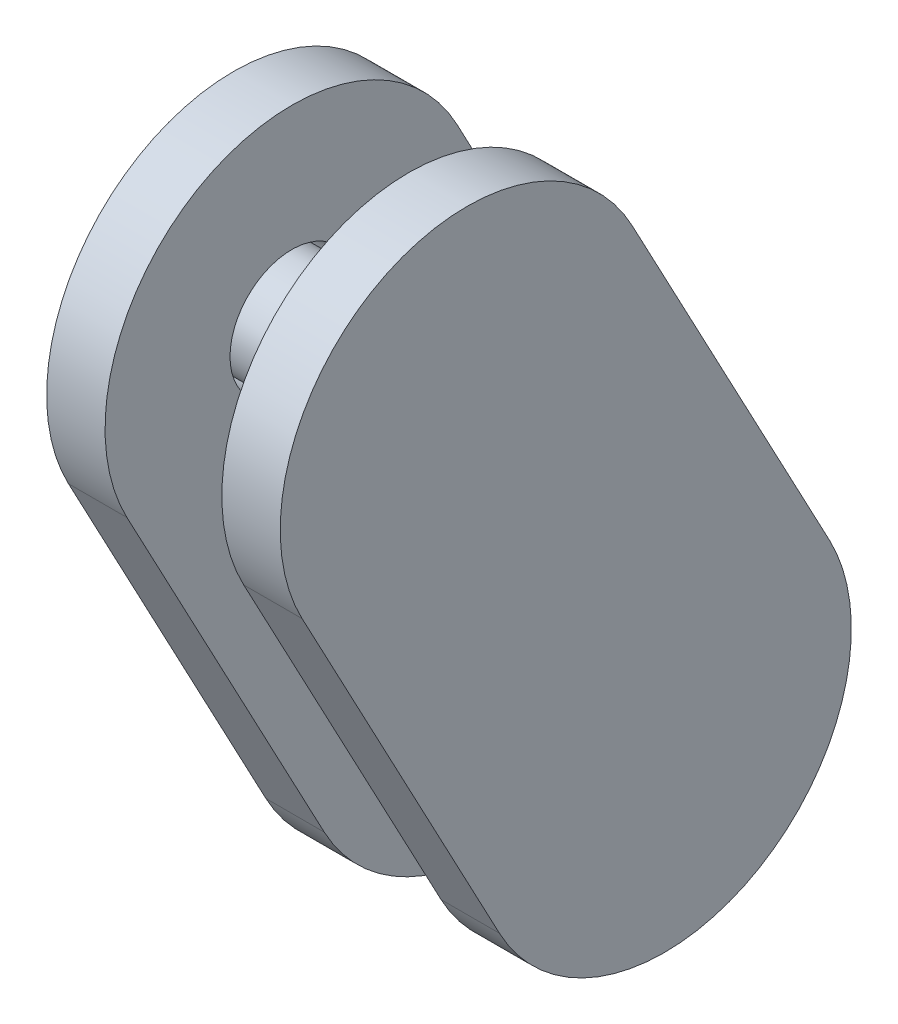
SolidWorks part; units mm, degrees
ref_plane "Front Plane" through (0, 0, 0) normal (0, 0, 1) x (1, 0, 0)
ref_plane "Top Plane" through (0, 0, 0) normal (0, 1, 0) x (1, 0, 0)
ref_plane "Right Plane" through (0, 0, 0) normal (1, 0, 0) x (0, 0, -1)
sketch "Sketch1" plane through (23.5048, 0, 0) normal (1, 0, 0) x (0, 0, -1)
  line L0 (-8.0962, 116.6813) -> (0.3543, 100.7882) construction
  line L1 (-1.0326, 120.437) -> (7.4179, 104.544)
  line L2 (-15.1598, 112.9255) -> (-6.7093, 97.0324)
  arc A0 (-1.0326, 120.437) -> (-15.1598, 112.9255) centre (-8.0962, 116.6813) ccw
  arc A1 (-6.7093, 97.0324) -> (7.4179, 104.544) centre (0.3543, 100.7882) ccw
  point P4 (-3.8709, 108.7347)
  dimension "D1" = 16
extrude "Boss-Extrude1" add sketch "Sketch1" along normal blind 2.5
sketch "Sketch2" plane through (23.5048, 0, 0) normal (-1, 0, 0) x (0, 0, 1)
  circle A5 centre (8.0962, 116.6813) radius 2.35
  circle A6 centre (8.0962, 116.6813) radius 2.35
  circle A8 centre (-0.3543, 100.7882) radius 2.35
  circle A9 centre (-0.3543, 100.7882) radius 2.35
  dimension "D1" = 0.3
  dimension "D2" = 0.3
extrude "Boss-Extrude2" add sketch "Sketch2" along normal blind 7.5
sketch "Sketch3" plane through (18.5048, 0, 0) normal (-1, 0, 0) x (0, 0, 1)
  line L2 (1.0326, 120.437) -> (-7.4179, 104.544)
  line L3 (6.7093, 97.0324) -> (15.1598, 112.9255)
  line L4 (1.0326, 120.437) -> (-7.4179, 104.544)
  line L5 (6.7093, 97.0324) -> (15.1598, 112.9255)
  circle A0 centre (8.0962, 116.6813) radius 2.65 construction
  circle A1 centre (-0.3543, 100.7882) radius 2.65 construction
  arc A2 (15.1598, 112.9255) -> (1.0326, 120.437) centre (8.0962, 116.6813) ccw
  arc A3 (-7.4179, 104.544) -> (6.7093, 97.0324) centre (-0.3543, 100.7882) ccw
  arc A4 (15.1598, 112.9255) -> (1.0326, 120.437) centre (8.0962, 116.6813) ccw
  arc A5 (-7.4179, 104.544) -> (6.7093, 97.0324) centre (-0.3543, 100.7882) ccw
  circle A6 centre (8.0962, 116.6813) radius 2.65
  circle A7 centre (-0.3543, 100.7882) radius 2.65
  dimension "D1" = 0
extrude "Boss-Extrude3" add sketch "Sketch3" along normal blind 2.5 separate body
move or copy body "Body-Move/Copy1" bodies to move or copy 102 103 copy no translate (-21, -116.68, -8.1)
